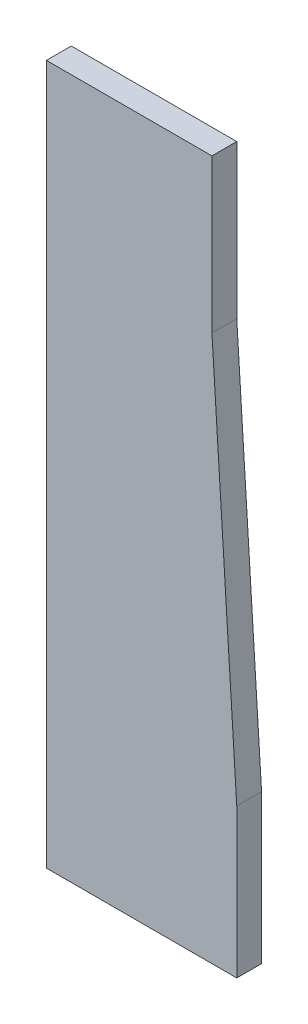
SolidWorks part; units mm, degrees
material "MDF"
ref_plane "Front Plane" through (0, 0, 0) normal (0, 0, 1) x (1, 0, 0)
ref_plane "Top Plane" through (0, 0, 0) normal (0, 1, 0) x (1, 0, 0)
ref_plane "Right Plane" through (0, 0, 0) normal (1, 0, 0) x (0, 0, -1)
sketch "Sketch1" plane through (0, 0, 0) normal (0, 0, 1) x (1, 0, 0)
  line L0 (82.0395, -5040.3314) -> (82.0395, -5577.1295)
  line L1 (82.0395, -5040.3314) -> (82.0395, -5480.4165) construction
  line L8 (-209.0395, -5040.3314) -> (-209.0395, -5158.0058)
  line L9 (-209.0395, -5158.0058) -> (-228.0888, -5462.7947)
  line L10 (-228.0888, -5462.7947) -> (-228.0888, -5577.1295)
  line L11 (-228.0888, -5577.1295) -> (228.0888, -5577.1295)
  line L12 (228.0888, -5577.1295) -> (228.0888, -5462.7947)
  line L13 (228.0888, -5462.7947) -> (209.0395, -5158.0058)
  line L14 (209.0395, -5158.0058) -> (209.0395, -5040.3314)
  line L15 (209.0395, -5040.3314) -> (-209.0395, -5040.3314)
  line L19 (82.0395, -5577.1295) -> (228.0888, -5577.1295)
  line L20 (228.0888, -5577.1295) -> (228.0888, -5462.7947)
  line L21 (228.0888, -5462.7947) -> (209.0395, -5158.0058)
  line L22 (209.0395, -5158.0058) -> (209.0395, -5040.3314)
  line L23 (209.0395, -5040.3314) -> (82.0395, -5040.3314)
  dimension "D1" = 0
extrude "Boss-Extrude1" add sketch "Sketch1" along normal blind 19.05
